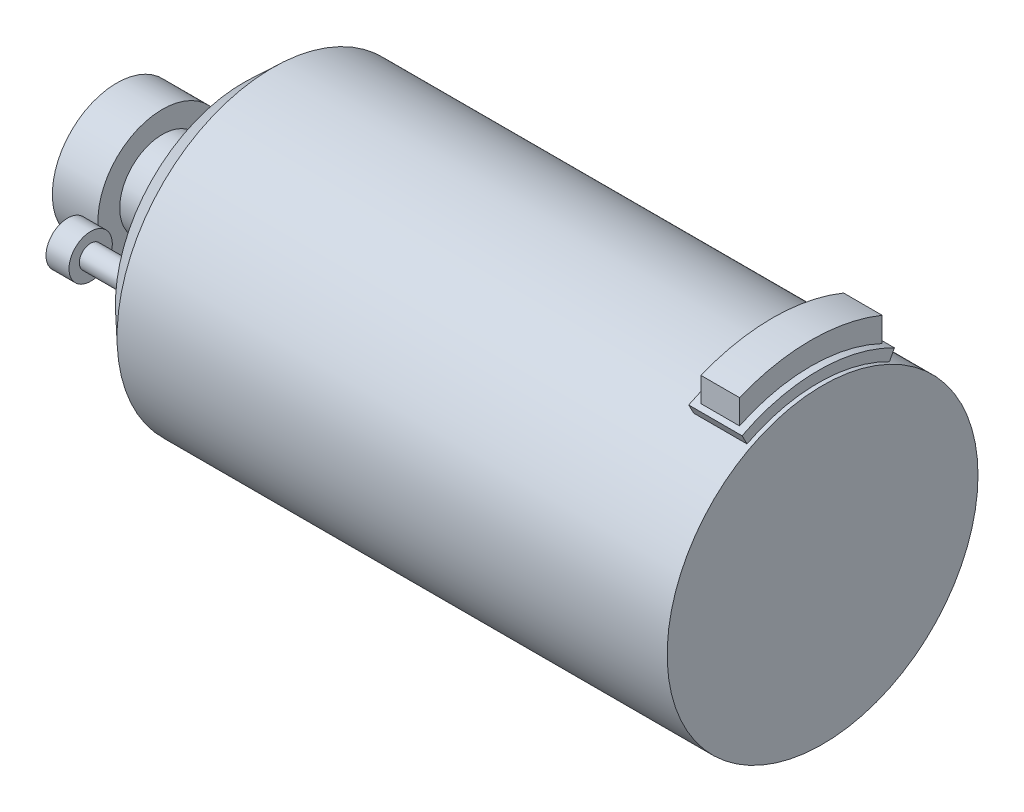
SolidWorks part; units mm, degrees
ref_plane "Front Plane" through (0, 0, 0) normal (0, 0, 1) x (1, 0, 0)
ref_plane "Top Plane" through (0, 0, 0) normal (0, 1, 0) x (1, 0, 0)
ref_plane "Right Plane" through (0, 0, 0) normal (1, 0, 0) x (0, 0, -1)
sketch "Sketch1" plane through (0, 0, 0) normal (0, 0, 1) x (1, 0, 0)
  line L0 (-46.8943, 0) -> (94.6404, 0) construction
  line L1 (94.6404, 0) -> (94.6404, 19.9771) construction
  line L2 (94.6404, 19.9771) -> (23.9268, 19.9771) construction
  line L3 (23.9268, 19.9771) -> (20.1676, 16.4257) construction
  line L4 (20.1676, 16.4257) -> (20.1676, 2.5146) construction
  line L5 (20.1676, 2.5146) -> (17.907, 2.5146) construction
  line L6 (17.907, 2.5146) -> (17.907, 5.4864) construction
  line L7 (17.907, 5.4864) -> (9.779, 5.4864) construction
  line L8 (9.779, 5.4864) -> (9.779, 8.2804) construction
  line L9 (9.779, 8.2804) -> (3.9116, 8.2804) construction
  line L10 (3.9116, 8.2804) -> (3.9116, 2.5146) construction
  line L11 (3.9116, 2.5146) -> (0, 2.5146) construction
  line L12 (0, 2.5146) -> (0, 0) construction
  line L13 (94.6404, 0) -> (94.6404, 19.9771)
  line L14 (94.6404, 19.9771) -> (23.9268, 19.9771)
  line L15 (23.9268, 19.9771) -> (20.1676, 16.4257)
  line L16 (20.1676, 16.4257) -> (20.1676, 2.5146)
  line L17 (20.1676, 2.5146) -> (17.907, 2.5146)
  line L18 (17.907, 2.5146) -> (17.907, 5.4864)
  line L19 (17.907, 5.4864) -> (9.779, 5.4864)
  line L20 (9.779, 5.4864) -> (9.779, 8.2804)
  line L21 (9.779, 8.2804) -> (3.9116, 8.2804)
  line L22 (3.9116, 8.2804) -> (3.9116, 2.5146)
  line L23 (3.9116, 2.5146) -> (0, 2.5146)
  line L24 (0, 2.5146) -> (0, 0)
  line L25 (94.6404, 0) -> (0, 0)
  dimension "D1" = 94.6404
  dimension "D2" = 19.9771
  dimension "D3" = 70.7136
  dimension "D4" = 3.7592
  dimension "D5" = 5.4864
  dimension "D6" = 8.128
  dimension "D7" = 5.8674
  dimension "D8" = 3.5514
  dimension "D9" = 2.5146
  dimension "D10" = 3.9116
  dimension "D11" = 8.2804
revolve "Revolve1" add sketch "Sketch1" angle 360 about L25
ref_plane "Plane2" through (90.6526, 0, 0) normal (1, 0, 0) x (0, 0, -1)
sketch "Sketch3" plane through (90.6526, 0, 0) normal (1, 0, 0) x (0, 0, -1)
  line L0 (-9.7917, 18.985) -> (-9.1572, 17.7547)
  line L1 (9.7917, 18.985) -> (9.1572, 17.7547)
  line L2 (0, 0) -> (-9.1572, 17.7547) construction
  line L3 (0, 0) -> (9.1572, 17.7547) construction
  line L4 (0, 0) -> (0, 19.9771) construction
  line L5 (-9.1572, 17.7547) -> (0, 19.9771) construction
  line L6 (0, 19.9771) -> (9.1572, 17.7547) construction
  arc A0 (9.7917, 18.985) -> (-9.7917, 18.985) centre (0, 0) ccw
  circle A4 centre (0, 0) radius 19.9771 construction
  circle A6 centre (0, 0) radius 19.9771
  arc A7 (-9.1572, 17.7547) -> (9.1572, 17.7547) centre (0, 0) ccw
  dimension "D1" = 42.7228
  dimension "D2" = 19.5834
  dimension "D3" = 1.3843
  dimension "D4" = 0
extrude "Boss-Extrude1" add sketch "Sketch3" along normal mid plane 6.858
sketch "Sketch4" plane through (90.6526, 0, 0) normal (1, 0, 0) x (0, 0, -1)
  line L0 (-9.1694, 19.2933) -> (-9.1694, 22.4429)
  line L1 (9.1694, 19.2933) -> (9.1694, 22.4429)
  line L4 (-9.7917, 18.985) -> (-9.1572, 17.7547)
  line L5 (9.1572, 17.7547) -> (9.7917, 18.985)
  line L6 (-9.7917, 18.985) -> (-9.1572, 17.7547)
  line L7 (9.1572, 17.7547) -> (9.7917, 18.985)
  arc A0 (9.7917, 18.985) -> (-9.7917, 18.985) centre (0, 0) ccw construction
  arc A1 (-9.1694, 22.4429) -> (9.1694, 22.4429) centre (0, 0) cw
  arc A2 (9.7917, 18.985) -> (9.1694, 19.2933) centre (0, 0) ccw
  arc A4 (9.1572, 17.7547) -> (-9.1572, 17.7547) centre (0, 0) ccw
  arc A5 (9.7917, 18.985) -> (-9.7917, 18.985) centre (0, 0) ccw
  arc A6 (9.1572, 17.7547) -> (-9.1572, 17.7547) centre (0, 0) ccw
  arc A7 (-9.1694, 19.2933) -> (-9.7917, 18.985) centre (0, 0) ccw
  dimension "D1" = 3.1496
  dimension "D2" = 18.3388
  dimension "D3" = 0
extrude "Boss-Extrude2" add sketch "Sketch4" along normal mid plane 4.953
sketch "Sketch7" plane through (20.1676, 0, 0) normal (-1, 0, 0) x (0, 0, 1)
  line L0 (-12.7, 0) -> (12.7, 0) construction
  circle A0 centre (-12.7, 0) radius 1.4605
  circle A1 centre (12.7, 0) radius 1.4605
  dimension "D2" = 2.921
  dimension "D1" = 25.4
extrude "Boss-Extrude5" add sketch "Sketch7" along normal blind 6.9088
sketch "Sketch8" plane through (13.2588, 0, 0) normal (-1, 0, 0) x (0, 0, 1)
  circle A0 centre (12.7, 0) radius 2.7813
  circle A1 centre (-12.7, 0) radius 2.7813
  dimension "D1" = 5.5626
extrude "Boss-Extrude6" add sketch "Sketch8" along normal blind 2.9591
sketch "Sketch10" plane through (3.9116, 0, 0) normal (-1, 0, 0) x (0, 0, 1)
  line L0 (0, 22.6889) -> (0, -23.19) construction
sketch "Sketch12" plane through (20.1676, 0, 0) normal (-1, 0, 0) x (0, 0, 1)
  line L0 (-14.1605, -4.2688) -> (-14.1605, 3.4546) construction
  circle A0 centre (-12.7, 0) radius 1.4605 construction
